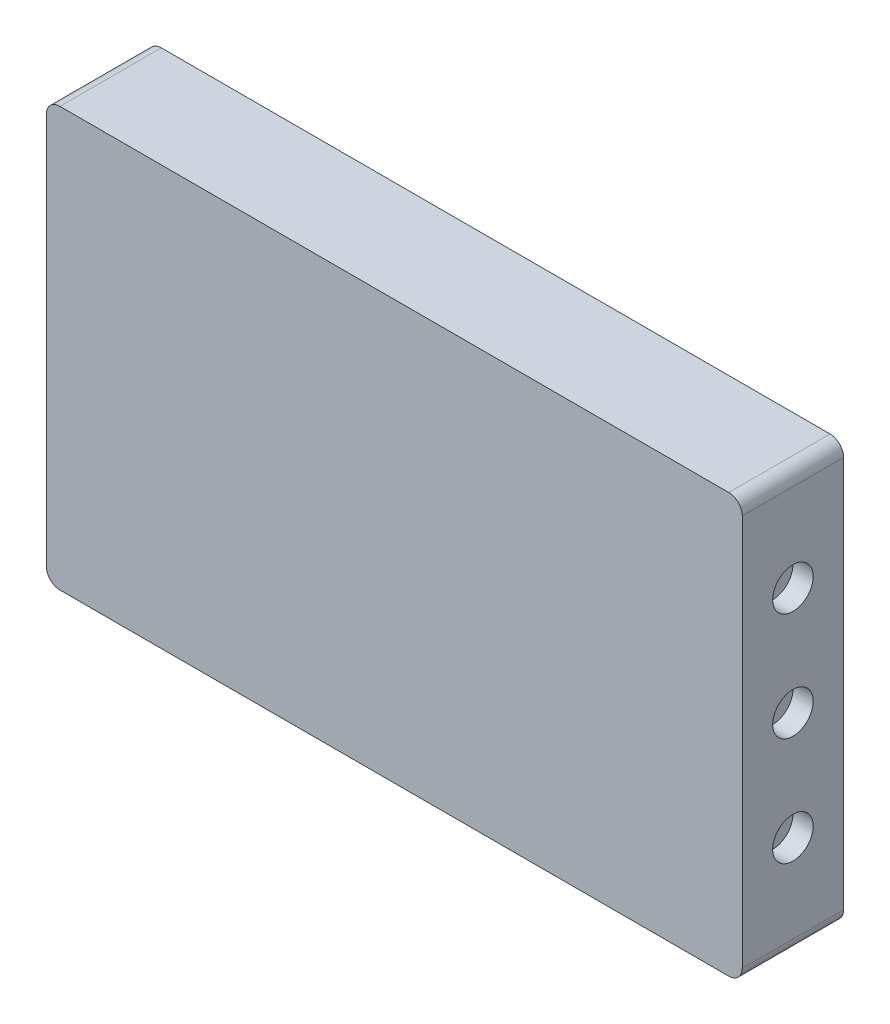
SolidWorks part; units mm, degrees
ref_plane "前视基准面" through (0, 0, 0) normal (0, 0, 1) x (1, 0, 0)
ref_plane "上视基准面" through (0, 0, 0) normal (0, 1, 0) x (1, 0, 0)
ref_plane "右视基准面" through (0, 0, 0) normal (1, 0, 0) x (0, 0, -1)
sketch "草图1" plane through (0, 0, 0) normal (0, 0, 1) x (1, 0, 0)
  line L1 (-51.5, -31) -> (51.5, -31)
  line L2 (-51.5, -31) -> (-51.5, 31)
  line L3 (-51.5, 31) -> (51.5, 31)
  line L4 (51.5, -31) -> (51.5, 31)
  line L5 (-51.5, -31) -> (51.5, 31) construction
  line L6 (-51.5, 31) -> (51.5, -31) construction
  point P0 (0, 0)
  dimension "D1" = 103
  dimension "D2" = 62
extrude "凸台-拉伸1" add sketch "草图1" along normal blind 15
fillet "圆角1" radius 2 4 edges at (-51.5, -31, 7.5) (51.5, -31, 7.5) (51.5, 31, 7.5) (-51.5, 31, 7.5)
sketch "草图2" plane through (51.5, 0, 0) normal (1, 0, 0) x (0, 0, -1)
  line L0 (-7.5, -31) -> (-7.5, 31) construction
  line L1 (0, -31) -> (-15, -31) construction
  line L2 (-15, 31) -> (0, 31) construction
  circle A0 centre (-7.5, 0) radius 3
  circle A1 centre (-7.5, 16) radius 3
  circle A2 centre (-7.5, -16) radius 3
  dimension "D1" = 16
  dimension "D2" = 16
extrude "切除-拉伸1" cut sketch "草图2" against normal blind 3
